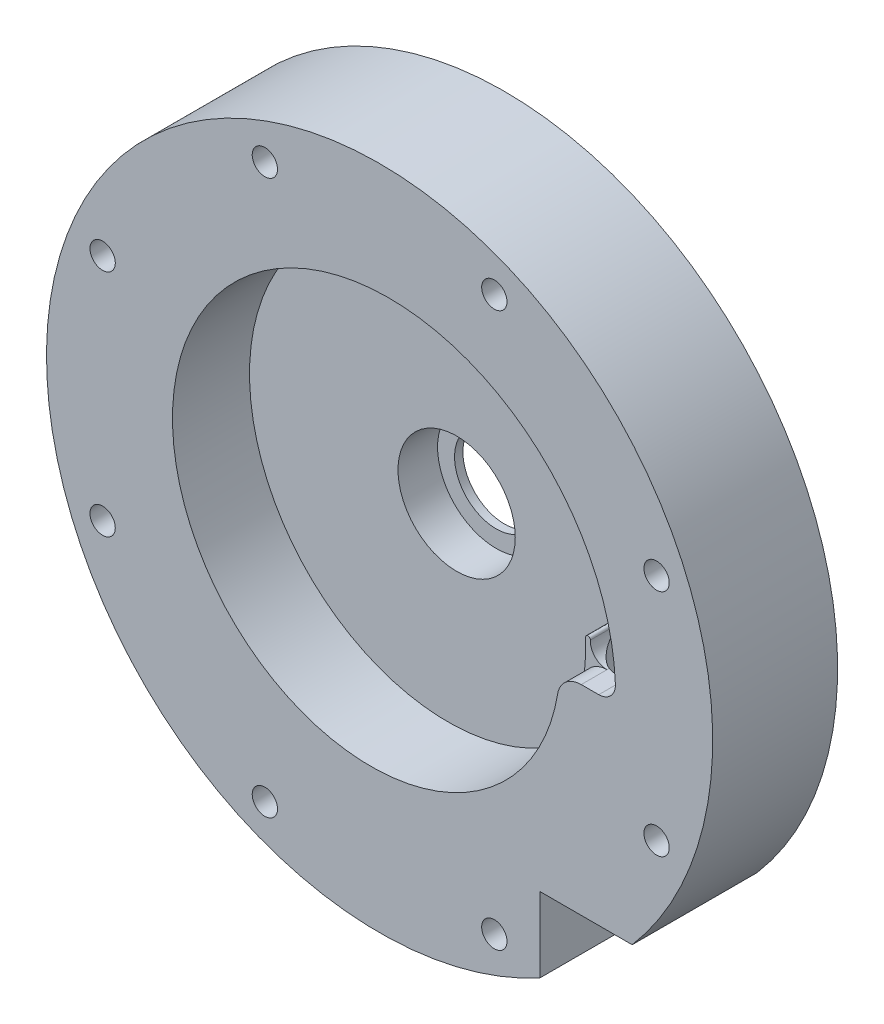
SolidWorks part; units mm, degrees
ref_plane "Front Plane" through (0, 0, 0) normal (0, 0, 1) x (1, 0, 0)
ref_plane "Top Plane" through (0, 0, 0) normal (0, 1, 0) x (1, 0, 0)
ref_plane "Right Plane" through (0, 0, 0) normal (1, 0, 0) x (0, 0, -1)
curve "Volute Spiral"
sketch "Sketch22" plane through (0, 0, 0) normal (0, 1, 0) x (1, 0, 0)
  line L0 (-25.4, 0) -> (-11.176, 0)
  line L1 (-25.4, 0) -> (-25.4, -14.6844)
  line L3 (-25.4, -14.6844) -> (-63.5, -14.6844)
  line L4 (-63.5, -14.6844) -> (-63.5, 9.1281)
  line L5 (-11.176, 0) -> (-11.176, 7.5406)
  line L7 (-11.176, 7.5406) -> (-7.9375, 7.5406)
  line L8 (-7.9375, 7.5406) -> (-7.9375, 9.1281)
  line L9 (-7.9375, 9.1281) -> (-63.5, 9.1281)
  line L10 (0, 0) -> (0, 9.525) construction
  dimension "D1" = 15.875
  dimension "D2" = 22.352
  dimension "D3" = 7.5406
  dimension "D4" = 1.5875
  dimension "D5" = 50.8
  dimension "D6" = 127
  dimension "D7" = 23.8125
revolve "Revolve1" add sketch "Sketch22" angle 360 about L10
sketch "Sketch23" plane through (0, 0, 0) normal (0, 0, 1) x (1, 0, 0)
  line L0 (38.4379, -3.3053) -> (41.7745, -3.3053)
  arc A0 (34.3588, 0) -> (35.2656, 0) centre (34.8122, 0.0186) cw
  arc A1 (35.2656, 0) -> (38.4379, -3.3053) centre (38.4379, -0.1303) ccw
  arc A3 (41.7745, -3.3053) -> (44.9468, 0) centre (41.7745, -0.1303) ccw
  spline S0 degree 3 poles (2030.6702, 117.5627) (22.8425, 27.2702) (33.9059, 13.6563) (34.3749, -0.4324) (34.3809, -0.6488) (34.39, -1.0819) (34.3957, -2.0941) (34.3424, -3.6139) (34.1824, -5.4201) (33.9415, -7.1482) (33.6134, -8.8659) (33.1986, -10.5687) (32.6976, -12.2522) (32.1114, -13.9121) (31.441, -15.5441) (30.6877, -17.144) (29.8532, -18.7074) (28.939, -20.2303) (27.9473, -21.7085) (26.88, -23.1383) (25.7397, -24.5156) (24.5289, -25.8368) (23.2503, -27.0983) (21.9069, -28.2965) (20.5017, -29.4282) (19.0382, -30.4901) (17.5197, -31.4792) (15.9499, -32.3928) (14.3324, -33.228) (12.6714, -33.9826) (10.9706, -34.6541) (9.2344, -35.2405) (7.4669, -35.7399) (5.6726, -36.1506) (3.8558, -36.4713) (2.0211, -36.7006) (0.1731, -36.8377) (-1.6836, -36.8816) (-3.5443, -36.832) (-5.4042, -36.6885) (-7.2587, -36.451) (-9.103, -36.1198) (-10.9323, -35.6953) (-12.7419, -35.1781) (-14.5271, -34.5691) (-16.2833, -33.8695) (-18.0059, -33.0806) (-19.6903, -32.2042) (-21.3321, -31.2419) (-22.9268, -30.1959) (-24.4703, -29.0686) (-25.9584, -27.8623) (-27.387, -26.5798) (-28.7522, -25.2241) (-30.0503, -23.7982) (-31.2777, -22.3056) (-32.4309, -20.7497) (-33.5067, -19.1341) (-34.502, -17.4628) (-35.4138, -15.7398) (-36.2396, -13.9692) (-36.9769, -12.1553) (-37.6233, -10.3026) (-38.1768, -8.4156) (-38.6356, -6.499) (-38.9982, -4.5575) (-39.2631, -2.596) (-39.4293, -0.6193) (-39.496, 1.3675) (-39.4624, 3.3595) (-39.3284, 5.3515) (-39.0938, 7.3386) (-38.7587, 9.3155) (-38.3235, 11.2774) (-37.7891, 13.219) (-37.1561, 15.1353) (-36.426, 17.0214) (-35.6001, 18.8723) (-34.6801, 20.6832) (-33.6679, 22.4492) (-32.5657, 24.1657) (-31.376, 25.8281) (-30.1015, 27.4319) (-28.7449, 28.9728) (-27.3094, 30.4465) (-25.7983, 31.8492) (-24.2152, 33.1767) (-22.5637, 34.4256) (-20.8479, 35.5922) (-19.0717, 36.6732) (-17.2395, 37.6655) (-15.3557, 38.5662) (-13.4249, 39.3727) (-11.4518, 40.0824) (-9.4412, 40.6932) (-7.3981, 41.203) (-5.3277, 41.6102) (-3.2349, 41.9133) (-1.1252, 42.1111) (0.9963, 42.2026) (3.1241, 42.1871) (5.2529, 42.0643) (7.3772, 41.834) (9.4917, 41.4964) (11.5908, 41.0518) (13.6692, 40.5009) (15.7214, 39.8448) (17.7422, 39.0846) (19.7263, 38.2218) (21.6685, 37.2583) (23.5635, 36.196) (25.4065, 35.0373) (27.1926, 33.7847) (28.9168, 32.441) (30.5746, 31.0093) (32.1614, 29.4928) (33.673, 27.8951) (35.1052, 26.2198) (36.454, 24.4711) (37.7156, 22.6529) (38.8865, 20.7697) (39.9633, 18.8259) (40.9428, 16.8264) (41.8222, 14.7759) (42.5989, 12.6795) (43.2704, 10.5424) (43.8346, 8.3697) (44.2896, 6.1669) (44.6194, 4.0326) (44.7887, 2.4435) (44.8619, 1.5054) (44.8876, 1.1295) (44.9051, 0.8474) (44.9209, 0.5651) (45.7546, -16.1489) (34.874, -33.296) (2043.9896, 40.6272) knots -0.167581 -0.167581 -0.167581 -0.167581 0.000871 0.001741 0.002613 0.003484 0.006972 0.014833 0.021837 0.028857 0.035892 0.042943 0.05001 0.057093 0.064191 0.071305 0.078435 0.085581 0.092743 0.099921 0.107115 0.114325 0.121551 0.128793 0.136052 0.143327 0.150618 0.157925 0.165249 0.172589 0.179945 0.187318 0.194707 0.202113 0.209535 0.216974 0.22443 0.231902 0.23939 0.246895 0.254417 0.261956 0.269511 0.277083 0.284672 0.292277 0.2999 0.307539 0.315195 0.322868 0.330558 0.338265 0.345988 0.353729 0.361487 0.369261 0.377053 0.384862 0.392688 0.400531 0.408391 0.416268 0.424163 0.432075 0.440003 0.447949 0.455913 0.463893 0.471891 0.479906 0.487939 0.495989 0.504056 0.512141 0.520243 0.528362 0.536499 0.544653 0.552825 0.561015 0.569221 0.577446 0.585688 0.593947 0.602224 0.610519 0.618831 0.627161 0.635509 0.643874 0.652257 0.660658 0.669076 0.677513 0.685967 0.694438 0.702928 0.711435 0.71996 0.728503 0.737064 0.745643 0.75424 0.762854 0.771487 0.780137 0.788806 0.797492 0.806197 0.814919 0.823659 0.832418 0.841194 0.849989 0.858802 0.867633 0.876481 0.885349 0.894234 0.903137 0.912059 0.920998 0.929956 0.938933 0.947927 0.95694 0.965971 0.97502 0.984088 0.992037 0.994311 0.995448 0.996585 0.997723 0.998862 1.19863 1.19863 1.19863 1.19863 only from (34.3588, 0) to (44.9468, 0) construction
  spline S1 degree 3 poles (34.3588, 0) (34.3618, -0.072) (34.3677, -0.2162) (34.3749, -0.4324) (34.3809, -0.6488) (34.39, -1.0819) (34.3957, -2.0941) (34.3424, -3.6139) (34.1824, -5.4201) (33.9415, -7.1482) (33.6134, -8.8659) (33.1986, -10.5687) (32.6976, -12.2522) (32.1114, -13.9121) (31.441, -15.5441) (30.6877, -17.144) (29.8532, -18.7074) (28.939, -20.2303) (27.9473, -21.7085) (26.88, -23.1383) (25.7397, -24.5156) (24.5289, -25.8368) (23.2503, -27.0983) (21.9069, -28.2965) (20.5017, -29.4282) (19.0382, -30.4901) (17.5197, -31.4792) (15.9499, -32.3928) (14.3324, -33.228) (12.6714, -33.9826) (10.9706, -34.6541) (9.2344, -35.2405) (7.4669, -35.7399) (5.6726, -36.1506) (3.8558, -36.4713) (2.0211, -36.7006) (0.1731, -36.8377) (-1.6836, -36.8816) (-3.5443, -36.832) (-5.4042, -36.6885) (-7.2587, -36.451) (-9.103, -36.1198) (-10.9323, -35.6953) (-12.7419, -35.1781) (-14.5271, -34.5691) (-16.2833, -33.8695) (-18.0059, -33.0806) (-19.6903, -32.2042) (-21.3321, -31.2419) (-22.9268, -30.1959) (-24.4703, -29.0686) (-25.9584, -27.8623) (-27.387, -26.5798) (-28.7522, -25.2241) (-30.0503, -23.7982) (-31.2777, -22.3056) (-32.4309, -20.7497) (-33.5067, -19.1341) (-34.502, -17.4628) (-35.4138, -15.7398) (-36.2396, -13.9692) (-36.9769, -12.1553) (-37.6233, -10.3026) (-38.1768, -8.4156) (-38.6356, -6.499) (-38.9982, -4.5575) (-39.2631, -2.596) (-39.4293, -0.6193) (-39.496, 1.3675) (-39.4624, 3.3595) (-39.3284, 5.3515) (-39.0938, 7.3386) (-38.7587, 9.3155) (-38.3235, 11.2774) (-37.7891, 13.219) (-37.1561, 15.1353) (-36.426, 17.0214) (-35.6001, 18.8723) (-34.6801, 20.6832) (-33.6679, 22.4492) (-32.5657, 24.1657) (-31.376, 25.8281) (-30.1015, 27.4319) (-28.7449, 28.9728) (-27.3094, 30.4465) (-25.7983, 31.8492) (-24.2152, 33.1767) (-22.5637, 34.4256) (-20.8479, 35.5922) (-19.0717, 36.6732) (-17.2395, 37.6655) (-15.3557, 38.5662) (-13.4249, 39.3727) (-11.4518, 40.0824) (-9.4412, 40.6932) (-7.3981, 41.203) (-5.3277, 41.6102) (-3.2349, 41.9133) (-1.1252, 42.1111) (0.9963, 42.2026) (3.1241, 42.1871) (5.2529, 42.0643) (7.3772, 41.834) (9.4917, 41.4964) (11.5908, 41.0518) (13.6692, 40.5009) (15.7214, 39.8448) (17.7422, 39.0846) (19.7263, 38.2218) (21.6685, 37.2583) (23.5635, 36.196) (25.4065, 35.0373) (27.1926, 33.7847) (28.9168, 32.441) (30.5746, 31.0093) (32.1614, 29.4928) (33.673, 27.8951) (35.1052, 26.2198) (36.454, 24.4711) (37.7156, 22.6529) (38.8865, 20.7697) (39.9633, 18.8259) (40.9428, 16.8264) (41.8222, 14.7759) (42.5989, 12.6795) (43.2704, 10.5424) (43.8346, 8.3697) (44.2896, 6.1669) (44.6194, 4.0326) (44.7887, 2.4435) (44.8619, 1.5054) (44.8876, 1.1295) (44.9051, 0.8474) (44.9209, 0.5651) (44.935, 0.2826) (44.9429, 0.0942) (44.9468, 0) knots 0 0 0 0 0.000871 0.001741 0.002613 0.003484 0.006972 0.014833 0.021837 0.028857 0.035892 0.042943 0.05001 0.057093 0.064191 0.071305 0.078435 0.085581 0.092743 0.099921 0.107115 0.114325 0.121551 0.128793 0.136052 0.143327 0.150618 0.157925 0.165249 0.172589 0.179945 0.187318 0.194707 0.202113 0.209535 0.216974 0.22443 0.231902 0.23939 0.246895 0.254417 0.261956 0.269511 0.277083 0.284672 0.292277 0.2999 0.307539 0.315195 0.322868 0.330558 0.338265 0.345988 0.353729 0.361487 0.369261 0.377053 0.384862 0.392688 0.400531 0.408391 0.416268 0.424163 0.432075 0.440003 0.447949 0.455913 0.463893 0.471891 0.479906 0.487939 0.495989 0.504056 0.512141 0.520243 0.528362 0.536499 0.544653 0.552825 0.561015 0.569221 0.577446 0.585688 0.593947 0.602224 0.610519 0.618831 0.627161 0.635509 0.643874 0.652257 0.660658 0.669076 0.677513 0.685967 0.694438 0.702928 0.711435 0.71996 0.728503 0.737064 0.745643 0.75424 0.762854 0.771487 0.780137 0.788806 0.797492 0.806197 0.814919 0.823659 0.832418 0.841194 0.849989 0.858802 0.867633 0.876481 0.885349 0.894234 0.903137 0.912059 0.920998 0.929956 0.938933 0.947927 0.95694 0.965971 0.97502 0.984088 0.992037 0.994311 0.995448 0.996585 0.997723 0.998862 1 1 1 1
  dimension "D1" = 3.175
  dimension "D2" = 0.9068
extrude "Cut-Extrude1" cut sketch "Sketch23" along normal through all
ref_plane "Volute Height Plane" through (0, 0, 9.779) normal (0, 0, 1) x (1, 0, 0)
sketch "Sketch25" plane through (0, 0, 9.779) normal (0, 0, 1) x (1, 0, 0)
  line L0 (41.7745, -3.3053) -> (38.4379, -3.3053)
  arc A0 (38.4379, -3.3053) -> (33.9294, -7.1321) centre (38.4379, -7.8746) ccw
  arc A1 (41.7745, -3.3053) -> (44.9468, 0) centre (41.7745, -0.1303) ccw construction
  arc A2 (41.7745, -3.3053) -> (44.9468, 0) centre (41.7745, -0.1303) ccw
  arc A3 (35.2656, 0) -> (34.3588, 0) centre (34.8122, 0.0186) ccw construction
  arc A4 (35.2656, 0) -> (38.4379, -3.3053) centre (38.4379, -0.1303) ccw construction
  arc A5 (35.2656, 0) -> (34.3588, 0) centre (34.8122, 0.0186) ccw
  arc A6 (35.2656, 0) -> (38.4379, -3.3053) centre (38.4379, -0.1303) ccw
  spline S0 degree 3 poles (44.9468, 0) (44.9429, 0.0942) (44.935, 0.2826) (44.9209, 0.5651) (44.9051, 0.8474) (44.8876, 1.1295) (44.8619, 1.5054) (44.7887, 2.4435) (44.6194, 4.0326) (44.2896, 6.1669) (43.8346, 8.3697) (43.2704, 10.5424) (42.5989, 12.6795) (41.8222, 14.7759) (40.9428, 16.8264) (39.9633, 18.8259) (38.8865, 20.7697) (37.7156, 22.6529) (36.454, 24.4711) (35.1052, 26.2198) (33.673, 27.8951) (32.1614, 29.4928) (30.5746, 31.0093) (28.9168, 32.441) (27.1926, 33.7847) (25.4065, 35.0373) (23.5635, 36.196) (21.6685, 37.2583) (19.7263, 38.2218) (17.7422, 39.0846) (15.7214, 39.8448) (13.6692, 40.5009) (11.5908, 41.0518) (9.4917, 41.4964) (7.3772, 41.834) (5.2529, 42.0643) (3.1241, 42.1871) (0.9963, 42.2026) (-1.1252, 42.1111) (-3.2349, 41.9133) (-5.3277, 41.6102) (-7.3981, 41.203) (-9.4412, 40.6932) (-11.4518, 40.0824) (-13.4249, 39.3727) (-15.3557, 38.5662) (-17.2395, 37.6655) (-19.0717, 36.6732) (-20.8479, 35.5922) (-22.5637, 34.4256) (-24.2152, 33.1767) (-25.7983, 31.8492) (-27.3094, 30.4465) (-28.7449, 28.9728) (-30.1015, 27.4319) (-31.376, 25.8281) (-32.5657, 24.1657) (-33.6679, 22.4492) (-34.6801, 20.6832) (-35.6001, 18.8723) (-36.426, 17.0214) (-37.1561, 15.1353) (-37.7891, 13.219) (-38.3235, 11.2774) (-38.7587, 9.3155) (-39.0938, 7.3386) (-39.3284, 5.3515) (-39.4624, 3.3595) (-39.496, 1.3675) (-39.4293, -0.6193) (-39.2631, -2.596) (-38.9982, -4.5575) (-38.6356, -6.499) (-38.1768, -8.4156) (-37.6233, -10.3026) (-36.9769, -12.1553) (-36.2396, -13.9692) (-35.4138, -15.7398) (-34.502, -17.4628) (-33.5067, -19.1341) (-32.4309, -20.7497) (-31.2777, -22.3056) (-30.0503, -23.7982) (-28.7522, -25.2241) (-27.387, -26.5798) (-25.9584, -27.8623) (-24.4703, -29.0686) (-22.9268, -30.1959) (-21.3321, -31.2419) (-19.6903, -32.2042) (-18.0059, -33.0806) (-16.2833, -33.8695) (-14.5271, -34.5691) (-12.7419, -35.1781) (-10.9323, -35.6953) (-9.103, -36.1198) (-7.2587, -36.451) (-5.4042, -36.6885) (-3.5443, -36.832) (-1.6836, -36.8816) (0.1731, -36.8377) (2.0211, -36.7006) (3.8558, -36.4713) (5.6726, -36.1506) (7.4669, -35.7399) (9.2344, -35.2405) (10.9706, -34.6541) (12.6714, -33.9826) (14.3324, -33.228) (15.9499, -32.3928) (17.5197, -31.4792) (19.0382, -30.4901) (20.5017, -29.4282) (21.9069, -28.2965) (23.2503, -27.0983) (24.5289, -25.8368) (25.7397, -24.5156) (26.88, -23.1383) (27.9473, -21.7085) (28.939, -20.2303) (29.8532, -18.7074) (30.6877, -17.144) (31.441, -15.5441) (32.1114, -13.9121) (32.6976, -12.2522) (33.1986, -10.5687) (33.6134, -8.8659) (33.9415, -7.1482) (34.1824, -5.4201) (34.3424, -3.6139) (34.3957, -2.0941) (34.39, -1.0819) (34.3809, -0.6488) (34.3749, -0.4324) (34.3677, -0.2162) (34.3618, -0.072) (34.3588, 0) knots 0 0 0 0 0.001138 0.002277 0.003415 0.004552 0.005689 0.007963 0.015912 0.02498 0.034029 0.04306 0.052073 0.061067 0.070044 0.079002 0.087941 0.096863 0.105766 0.114651 0.123519 0.132367 0.141198 0.150011 0.158806 0.167582 0.176341 0.185081 0.193803 0.202508 0.211194 0.219863 0.228513 0.237146 0.24576 0.254357 0.262936 0.271497 0.28004 0.288565 0.297072 0.305562 0.314033 0.322487 0.330924 0.339342 0.347743 0.356126 0.364491 0.372839 0.381169 0.389481 0.397776 0.406053 0.414312 0.422554 0.430779 0.438985 0.447175 0.455347 0.463501 0.471638 0.479757 0.487859 0.495944 0.504011 0.512061 0.520094 0.528109 0.536107 0.544087 0.552051 0.559997 0.567925 0.575837 0.583732 0.591609 0.599469 0.607312 0.615138 0.622947 0.630739 0.638513 0.646271 0.654012 0.661735 0.669442 0.677132 0.684805 0.692461 0.7001 0.707723 0.715328 0.722917 0.730489 0.738044 0.745583 0.753105 0.76061 0.768098 0.77557 0.783026 0.790465 0.797887 0.805293 0.812682 0.820055 0.827411 0.834751 0.842075 0.849382 0.856673 0.863948 0.871207 0.878449 0.885675 0.892885 0.900079 0.907257 0.914419 0.921565 0.928695 0.935809 0.942907 0.94999 0.957057 0.964108 0.971143 0.978163 0.985167 0.993028 0.996516 0.997387 0.998259 0.999129 1 1 1 1 construction
  spline S1 degree 3 poles (2044.2643, 40.6373) (34.873, -33.2976) (45.7547, -16.1496) (44.9209, 0.5651) (44.9051, 0.8474) (44.8876, 1.1295) (44.8619, 1.5054) (44.7887, 2.4435) (44.6194, 4.0326) (44.2896, 6.1669) (43.8346, 8.3697) (43.2704, 10.5424) (42.5989, 12.6795) (41.8222, 14.7759) (40.9428, 16.8264) (39.9633, 18.8259) (38.8865, 20.7697) (37.7156, 22.6529) (36.454, 24.4711) (35.1052, 26.2198) (33.673, 27.8951) (32.1614, 29.4928) (30.5746, 31.0093) (28.9168, 32.441) (27.1926, 33.7847) (25.4065, 35.0373) (23.5635, 36.196) (21.6685, 37.2583) (19.7263, 38.2218) (17.7422, 39.0846) (15.7214, 39.8448) (13.6692, 40.5009) (11.5908, 41.0518) (9.4917, 41.4964) (7.3772, 41.834) (5.2529, 42.0643) (3.1241, 42.1871) (0.9963, 42.2026) (-1.1252, 42.1111) (-3.2349, 41.9133) (-5.3277, 41.6102) (-7.3981, 41.203) (-9.4412, 40.6932) (-11.4518, 40.0824) (-13.4249, 39.3727) (-15.3557, 38.5662) (-17.2395, 37.6655) (-19.0717, 36.6732) (-20.8479, 35.5922) (-22.5637, 34.4256) (-24.2152, 33.1767) (-25.7983, 31.8492) (-27.3094, 30.4465) (-28.7449, 28.9728) (-30.1015, 27.4319) (-31.376, 25.8281) (-32.5657, 24.1657) (-33.6679, 22.4492) (-34.6801, 20.6832) (-35.6001, 18.8723) (-36.426, 17.0214) (-37.1561, 15.1353) (-37.7891, 13.219) (-38.3235, 11.2774) (-38.7587, 9.3155) (-39.0938, 7.3386) (-39.3284, 5.3515) (-39.4624, 3.3595) (-39.496, 1.3675) (-39.4293, -0.6193) (-39.2631, -2.596) (-38.9982, -4.5575) (-38.6356, -6.499) (-38.1768, -8.4156) (-37.6233, -10.3026) (-36.9769, -12.1553) (-36.2396, -13.9692) (-35.4138, -15.7398) (-34.502, -17.4628) (-33.5067, -19.1341) (-32.4309, -20.7497) (-31.2777, -22.3056) (-30.0503, -23.7982) (-28.7522, -25.2241) (-27.387, -26.5798) (-25.9584, -27.8623) (-24.4703, -29.0686) (-22.9268, -30.1959) (-21.3321, -31.2419) (-19.6903, -32.2042) (-18.0059, -33.0806) (-16.2833, -33.8695) (-14.5271, -34.5691) (-12.7419, -35.1781) (-10.9323, -35.6953) (-9.103, -36.1198) (-7.2587, -36.451) (-5.4042, -36.6885) (-3.5443, -36.832) (-1.6836, -36.8816) (0.1731, -36.8377) (2.0211, -36.7006) (3.8558, -36.4713) (5.6726, -36.1506) (7.4669, -35.7399) (9.2344, -35.2405) (10.9706, -34.6541) (12.6714, -33.9826) (14.3324, -33.228) (15.9499, -32.3928) (17.5197, -31.4792) (19.0382, -30.4901) (20.5017, -29.4282) (21.9069, -28.2965) (23.2503, -27.0983) (24.5289, -25.8368) (25.7397, -24.5156) (26.88, -23.1383) (27.9473, -21.7085) (28.939, -20.2303) (29.8532, -18.7074) (30.6877, -17.144) (31.441, -15.5441) (32.1114, -13.9121) (32.6976, -12.2522) (33.1986, -10.5687) (33.6134, -8.8659) (33.9415, -7.1482) (34.1824, -5.4201) (34.3424, -3.6139) (34.3957, -2.0941) (34.39, -1.0819) (34.3809, -0.6488) (34.3749, -0.4324) (33.906, 13.6558) (22.8434, 27.2691) (2030.4256, 117.5517) knots -0.198639 -0.198639 -0.198639 -0.198639 0.001138 0.002277 0.003415 0.004552 0.005689 0.007963 0.015912 0.02498 0.034029 0.04306 0.052073 0.061067 0.070044 0.079002 0.087941 0.096863 0.105766 0.114651 0.123519 0.132367 0.141198 0.150011 0.158806 0.167582 0.176341 0.185081 0.193803 0.202508 0.211194 0.219863 0.228513 0.237146 0.24576 0.254357 0.262936 0.271497 0.28004 0.288565 0.297072 0.305562 0.314033 0.322487 0.330924 0.339342 0.347743 0.356126 0.364491 0.372839 0.381169 0.389481 0.397776 0.406053 0.414312 0.422554 0.430779 0.438985 0.447175 0.455347 0.463501 0.471638 0.479757 0.487859 0.495944 0.504011 0.512061 0.520094 0.528109 0.536107 0.544087 0.552051 0.559997 0.567925 0.575837 0.583732 0.591609 0.599469 0.607312 0.615138 0.622947 0.630739 0.638513 0.646271 0.654012 0.661735 0.669442 0.677132 0.684805 0.692461 0.7001 0.707723 0.715328 0.722917 0.730489 0.738044 0.745583 0.753105 0.76061 0.768098 0.77557 0.783026 0.790465 0.797887 0.805293 0.812682 0.820055 0.827411 0.834751 0.842075 0.849382 0.856673 0.863948 0.871207 0.878449 0.885675 0.892885 0.900079 0.907257 0.914419 0.921565 0.928695 0.935809 0.942907 0.94999 0.957057 0.964108 0.971143 0.978163 0.985167 0.993028 0.996516 0.997387 0.998259 0.999129 1.167574 1.167574 1.167574 1.167574 only from (44.9468, 0) to (34.3588, 0) construction
  spline S2 degree 3 poles (44.9468, 0) (44.9429, 0.0942) (44.935, 0.2826) (44.9209, 0.5651) (44.9051, 0.8474) (44.8876, 1.1295) (44.8619, 1.5054) (44.7887, 2.4435) (44.6194, 4.0326) (44.2896, 6.1669) (43.8346, 8.3697) (43.2704, 10.5424) (42.5989, 12.6795) (41.8222, 14.7759) (40.9428, 16.8264) (39.9633, 18.8259) (38.8865, 20.7697) (37.7156, 22.6529) (36.454, 24.4711) (35.1052, 26.2198) (33.673, 27.8951) (32.1614, 29.4928) (30.5746, 31.0093) (28.9168, 32.441) (27.1926, 33.7847) (25.4065, 35.0373) (23.5635, 36.196) (21.6685, 37.2583) (19.7263, 38.2218) (17.7422, 39.0846) (15.7214, 39.8448) (13.6692, 40.5009) (11.5908, 41.0518) (9.4917, 41.4964) (7.3772, 41.834) (5.2529, 42.0643) (3.1241, 42.1871) (0.9963, 42.2026) (-1.1252, 42.1111) (-3.2349, 41.9133) (-5.3277, 41.6102) (-7.3981, 41.203) (-9.4412, 40.6932) (-11.4518, 40.0824) (-13.4249, 39.3727) (-15.3557, 38.5662) (-17.2395, 37.6655) (-19.0717, 36.6732) (-20.8479, 35.5922) (-22.5637, 34.4256) (-24.2152, 33.1767) (-25.7983, 31.8492) (-27.3094, 30.4465) (-28.7449, 28.9728) (-30.1015, 27.4319) (-31.376, 25.8281) (-32.5657, 24.1657) (-33.6679, 22.4492) (-34.6801, 20.6832) (-35.6001, 18.8723) (-36.426, 17.0214) (-37.1561, 15.1353) (-37.7891, 13.219) (-38.3235, 11.2774) (-38.7587, 9.3155) (-39.0938, 7.3386) (-39.3284, 5.3515) (-39.4624, 3.3595) (-39.496, 1.3675) (-39.4293, -0.6193) (-39.2631, -2.596) (-38.9982, -4.5575) (-38.6356, -6.499) (-38.1768, -8.4156) (-37.6233, -10.3026) (-36.9769, -12.1553) (-36.2396, -13.9692) (-35.4138, -15.7398) (-34.502, -17.4628) (-33.5067, -19.1341) (-32.4309, -20.7497) (-31.2777, -22.3056) (-30.0503, -23.7982) (-28.7522, -25.2241) (-27.387, -26.5798) (-25.9584, -27.8623) (-24.4703, -29.0686) (-22.9268, -30.1959) (-21.3321, -31.2419) (-19.6903, -32.2042) (-18.0059, -33.0806) (-16.2833, -33.8695) (-14.5271, -34.5691) (-12.7419, -35.1781) (-10.9323, -35.6953) (-9.103, -36.1198) (-7.2587, -36.451) (-5.4042, -36.6885) (-3.5443, -36.832) (-1.6836, -36.8816) (0.1731, -36.8377) (2.0211, -36.7006) (3.8558, -36.4713) (5.6726, -36.1506) (7.4669, -35.7399) (9.2344, -35.2405) (10.9706, -34.6541) (12.6714, -33.9826) (14.3324, -33.228) (15.9499, -32.3928) (17.5197, -31.4792) (19.0382, -30.4901) (20.5017, -29.4282) (21.9069, -28.2965) (23.2503, -27.0983) (24.5289, -25.8368) (25.7397, -24.5156) (26.88, -23.1383) (27.9473, -21.7085) (28.939, -20.2303) (29.8532, -18.7074) (30.6877, -17.144) (31.441, -15.5441) (32.1114, -13.9121) (32.6976, -12.2522) (33.1986, -10.5687) (33.6134, -8.8659) (33.9415, -7.1482) (34.1824, -5.4201) (34.3424, -3.6139) (34.3957, -2.0941) (34.39, -1.0819) (34.3809, -0.6488) (34.3749, -0.4324) (34.3677, -0.2162) (34.3618, -0.072) (34.3588, 0) knots 0 0 0 0 0.001138 0.002277 0.003415 0.004552 0.005689 0.007963 0.015912 0.02498 0.034029 0.04306 0.052073 0.061067 0.070044 0.079002 0.087941 0.096863 0.105766 0.114651 0.123519 0.132367 0.141198 0.150011 0.158806 0.167582 0.176341 0.185081 0.193803 0.202508 0.211194 0.219863 0.228513 0.237146 0.24576 0.254357 0.262936 0.271497 0.28004 0.288565 0.297072 0.305562 0.314033 0.322487 0.330924 0.339342 0.347743 0.356126 0.364491 0.372839 0.381169 0.389481 0.397776 0.406053 0.414312 0.422554 0.430779 0.438985 0.447175 0.455347 0.463501 0.471638 0.479757 0.487859 0.495944 0.504011 0.512061 0.520094 0.528109 0.536107 0.544087 0.552051 0.559997 0.567925 0.575837 0.583732 0.591609 0.599469 0.607312 0.615138 0.622947 0.630739 0.638513 0.646271 0.654012 0.661735 0.669442 0.677132 0.684805 0.692461 0.7001 0.707723 0.715328 0.722917 0.730489 0.738044 0.745583 0.753105 0.76061 0.768098 0.77557 0.783026 0.790465 0.797887 0.805293 0.812682 0.820055 0.827411 0.834751 0.842075 0.849382 0.856673 0.863948 0.871207 0.878449 0.885675 0.892885 0.900079 0.907257 0.914419 0.921565 0.928695 0.935809 0.942907 0.94999 0.957057 0.964108 0.971143 0.978163 0.985167 0.993028 0.996516 0.997387 0.998259 0.999129 1 1 1 1
extrude "Cut-Extrude2" cut sketch "Sketch25" along normal through all contours A2 S2 A5 A6 L0 | S2 A0 A6 A5
ref_plane "Outlet Plane" through (0, -41.4053, 0) normal (0, 1, 0) x (1, 0, 0)
sketch "Sketch7" plane through (0, -41.4053, 0) normal (0, 1, 0) x (1, 0, 0)
  line L0 (48.1441, -14.6844) -> (30.5812, -14.6844)
  line L1 (30.5812, -14.6844) -> (30.5812, 9.1281)
  line L2 (30.5812, 9.1281) -> (48.1441, 9.1281)
  line L3 (48.1441, 9.1281) -> (48.1441, -14.6844)
  line L8 (38.4379, -9.779) -> (41.7745, 0) construction
  point P11 (40.1062, -4.8895)
  dimension "D1" = 9.525
extrude "Outlet Cut" cut sketch "Sketch7" against normal through all
hole_wizard "3/8 (0.375) Diameter Hole1" positions "3DSketch2" profile "Sketch20" hole size "3/8" standard "ANSI Inch"
sketch3d "3DSketch2"
  line L0 (41.7745, -3.3053, 0) -> (38.4379, -3.3053, 9.779) construction
  point P0 (40.1062, -3.3053, 4.8895)
  point P11 (40.1062, -3.3053, 4.8895)
  point P20 (40.1062, -3.3053, 4.8895)
  point P22 (40.1062, -41.4053, 4.8895)
sketch "Sketch20" plane through (40.1062, -41.4053, 4.8895) normal (1, 0, 0) x (0, 0, -1)
  line L0 (0, 0) -> (0, 43.5016)
  line L1 (0, 43.5016) -> (4.7625, 40.64)
  line L2 (4.7625, 40.64) -> (4.7625, 0)
  line L5 (4.7625, 0) -> (0, 0)
  line L10 (0, 43.5016) -> (-4.7625, 40.64) construction
  line L11 (0, -6.35) -> (0, 107.95) construction
  dimension "Hole Dia." = 9.525
  dimension "Hole Depth" = 40.64
  dimension "Drill Angle" = 118
hole_wizard "Pipe Tap Drill for 3/8 Tap1" positions "3DSketch3" profile "Sketch21" hole size "3/8" standard "ANSI Inch"
sketch3d "3DSketch3"
  line L0 (35.3437, -41.4053, 4.8895) -> (44.8687, -41.4053, 4.8895) construction
  line L2 (40.1062, -41.4053, 0.127) -> (40.1062, -41.4053, 9.652) construction
  circle A0 centre (40.1062, -41.4053, 4.8895) radius 4.7625 construction
  point P2 (40.1062, -41.4053, 4.8895)
  point P9 (40.1062, -46.1678, 4.8895)
sketch "Sketch21" plane through (40.1062, -41.4053, 4.8895) normal (1, 0, 0) x (0, 0, -1)
  line L0 (0, 0) -> (0, 16.9886)
  line L1 (0, 16.9886) -> (7.1374, 12.7)
  line L2 (7.1374, 12.7) -> (7.1374, 0)
  line L5 (7.1374, 0) -> (0, 0)
  line L10 (0, 16.9886) -> (-7.1374, 12.7) construction
  line L11 (0, -6.35) -> (0, 107.95) construction
  dimension "Hole Dia." = 14.2748
  dimension "Hole Depth" = 12.7
  dimension "Drill Angle" = 118
sketch "Sketch16" plane through (0, 0, 14.6844) normal (0, 0, 1) x (1, 0, 0)
  circle A0 centre (0, 0) radius 47.625
  circle A1 centre (0, 0) radius 49.2125
  dimension "D1" = 95.25
  dimension "D2" = 98.425
sketch "Sketch26" plane through (0, 0, 14.6844) normal (0, 0, 1) x (1, 0, 0)
  line L0 (52.7997, -21.8704) -> (58.6664, -24.3004) construction
  line L1 (63.5, 0) -> (0, 0) construction
  circle A0 centre (52.7997, -21.8704) radius 2.413
  circle A1 centre (0, 0) radius 63.5 construction
  dimension "D1" = 4.826
  dimension "D2" = 6.35
  dimension "D3" = 22.5
extrude "Cut-Extrude3" cut sketch "Sketch26" against normal through all
pattern_circular "CirPattern1" count 8 over 360 about axis through (0, 0, 0) along (0, 0, 1) of "Cut-Extrude3"
